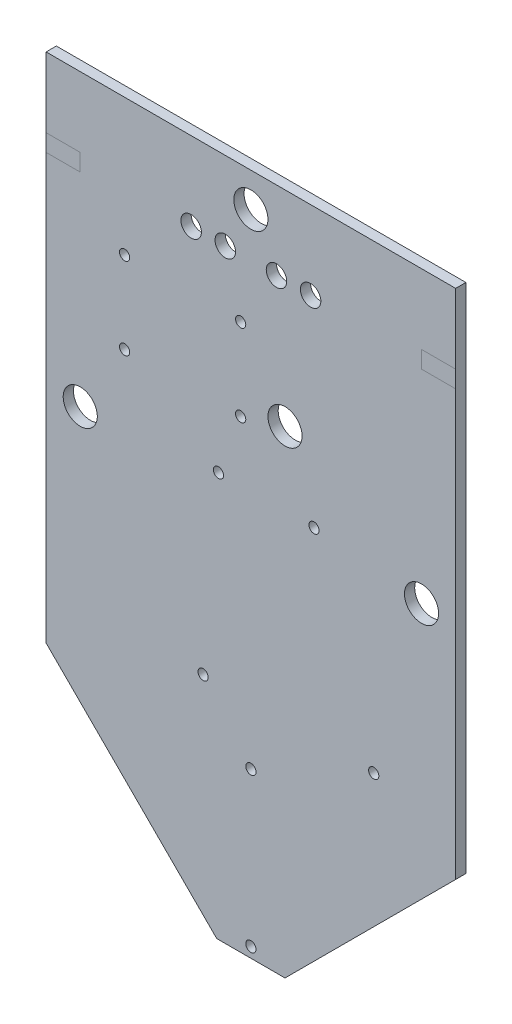
SolidWorks part; units mm, degrees
ref_plane "Plan de face" through (0, 0, 0) normal (0, 0, 1) x (1, 0, 0)
ref_plane "Plan de dessus" through (0, 0, 0) normal (0, 1, 0) x (1, 0, 0)
ref_plane "Plan de droite" through (0, 0, 0) normal (1, 0, 0) x (0, 0, -1)
sketch "Esquisse1" plane through (0, 0, 0) normal (0, 0, 1) x (1, 0, 0)
  line L0 (0, 0) -> (-120, 0)
  line L1 (-120, 0) -> (-120, -150)
  line L2 (-120, -150) -> (-70, -200)
  line L3 (-70, -200) -> (-50, -200)
  line L4 (-50, -200) -> (0, -150)
  line L5 (0, -150) -> (0, 0)
  dimension "D1" = 120
  dimension "D2" = 150
  dimension "D3" = 50
  dimension "D4" = 135
  dimension "D5" = 150
  dimension "D6" = 135
extrude "Extrusion1" add sketch "Esquisse1" along normal blind 3
sketch "Esquisse2" plane through (0, 0, 0) normal (0, 0, 1) x (1, 0, 0)
  line L0 (0, -150) -> (-73.9703, -150) construction
  line L4 (0, -150) -> (0, 0) construction
  circle A0 centre (-69.5, -81.5) radius 1.5
  circle A1 centre (-41.5, -81.5) radius 1.5
  circle A2 centre (-74, -135) radius 1.5
  circle A3 centre (-24, -135) radius 1.5
  dimension "D1" = 3
  dimension "D2" = 3
  dimension "D3" = 15
  dimension "D4" = 3
  dimension "D5" = 24
  dimension "D6" = 28
  dimension "D7" = 41.5
  dimension "D8" = 50
  dimension "D9" = 53.5
  dimension "D10" = 53.5
  dimension "D11" = 15
extrude "Enlèv. mat.-Extru.1" cut sketch "Esquisse2" along normal blind 16
sketch "Esquisse3" plane through (0, 0, 0) normal (0, 0, -1) x (-1, 0, 0)
  line L0 (0, -150) -> (0, 0) construction
  line L1 (0, 0) -> (120, 0) construction
  circle A0 centre (50, -60) radius 5
  dimension "D1" = 10
  dimension "D2" = 50
  dimension "D3" = 60
extrude "Enlèv. mat.-Extru.2" cut sketch "Esquisse3" against normal blind 16
sketch "Esquisse4" plane through (0, 0, 0) normal (0, 0, -1) x (-1, 0, 0)
  line L0 (120, 0) -> (0, -20) construction
  line L1 (0, -150) -> (20, -20) construction
  line L2 (100, -20) -> (120, -150) construction
  line L3 (0, -150) -> (0, 0) construction
  line L6 (0, 0) -> (120, 0) construction
  circle A0 centre (60, -10) radius 5
  circle A1 centre (10, -85) radius 5
  circle A2 centre (110, -85) radius 5
  dimension "D1" = 10
  dimension "D2" = 10
  dimension "D3" = 10
  dimension "D4" = 60
  dimension "D5" = 20
  dimension "D6" = 20
  dimension "D7" = 10
extrude "Enlèv. mat.-Extru.3" cut sketch "Esquisse4" against normal blind 16
sketch "Esquisse5" plane through (0, 0, 0) normal (0, 0, 1) x (1, 0, 0)
  line L2 (-97, -40) -> (-63, -40) construction
  line L3 (-63, -40) -> (-63, -64) construction
  line L4 (-63, -64) -> (-97, -64) construction
  line L5 (-97, -64) -> (-97, -40) construction
  line L6 (-120, 0) -> (-120, -150) construction
  line L7 (0, 0) -> (-120, 0) construction
  circle A0 centre (-97, -40) radius 1.5
  circle A1 centre (-63, -40) radius 1.5
  circle A2 centre (-63, -64) radius 1.5
  circle A3 centre (-97, -64) radius 1.5
  dimension "D1" = 3
  dimension "D2" = 3
  dimension "D3" = 3
  dimension "D4" = 3
  dimension "D5" = 23
  dimension "D6" = 40
  dimension "D7" = 34
  dimension "D8" = 24
extrude "Enlèv. mat.-Extru.4" cut sketch "Esquisse5" along normal blind 25.7922
sketch "Esquisse8" plane through (0, 0, 0) normal (0, 0, -1) x (-1, 0, 0)
  line L0 (42.5, -23) -> (56.115, -23) construction
  line L1 (60, 0) -> (60, -30.4584) construction
  line L2 (0, 0) -> (120, 0) construction
  circle A0 centre (52.5, -23) radius 3
  circle A1 centre (42.5, -23) radius 3
  circle A2 centre (67.5, -23) radius 3
  circle A3 centre (77.5, -23) radius 3
  dimension "D1" = 6
  dimension "D2" = 6
  dimension "D5" = 23
  dimension "D3" = 10
  dimension "D4" = 7.5
extrude "Enlèv. mat.-Extru.5" cut sketch "Esquisse8" against normal blind 8
sketch "Esquisse9" plane through (0, 0, 0) normal (0, 0, -1) x (-1, 0, 0)
  line L0 (60, -200) -> (60, -125.641) construction
  line L1 (70, -200) -> (50, -200) construction
  circle A0 centre (60, -152) radius 1.5
  circle A1 centre (60, -197) radius 1.5
  dimension "D2" = 3
  dimension "D3" = 3
  dimension "D1" = 45
  dimension "D4" = 3
extrude "Enlèv. mat.-Extru.6" cut sketch "Esquisse9" against normal blind 10
sketch "Esquisse11" plane through (0, 0, 3) normal (0, 0, 1) x (1, 0, 0)
  line L0 (-60, 0) -> (-60, -34.3167) construction
  line L1 (0, 0) -> (-120, 0) construction
  line L2 (-120, -20.5) -> (-110, -20.5)
  line L3 (-120, -20.5) -> (-120, -25.5)
  line L4 (-120, -25.5) -> (-110, -25.5)
  line L5 (-110, -20.5) -> (-110, -25.5)
  line L6 (-60, -23) -> (-92.2821, -23) construction
  line L7 (-92.2821, -23) -> (-110, -23) construction
  line L8 (-120, 0) -> (-120, -150) construction
  line L9 (-10, -20.5) -> (-10, -25.5)
  line L10 (0, -20.5) -> (0, -25.5)
  line L11 (0, -20.5) -> (-10, -20.5)
  line L12 (0, -25.5) -> (-10, -25.5)
  dimension "D1" = 10
  dimension "D2" = 23
  dimension "D3" = 5
extrude "Enlèv. mat.-Extru.9" cut sketch "Esquisse11" against normal blind 0.0001
